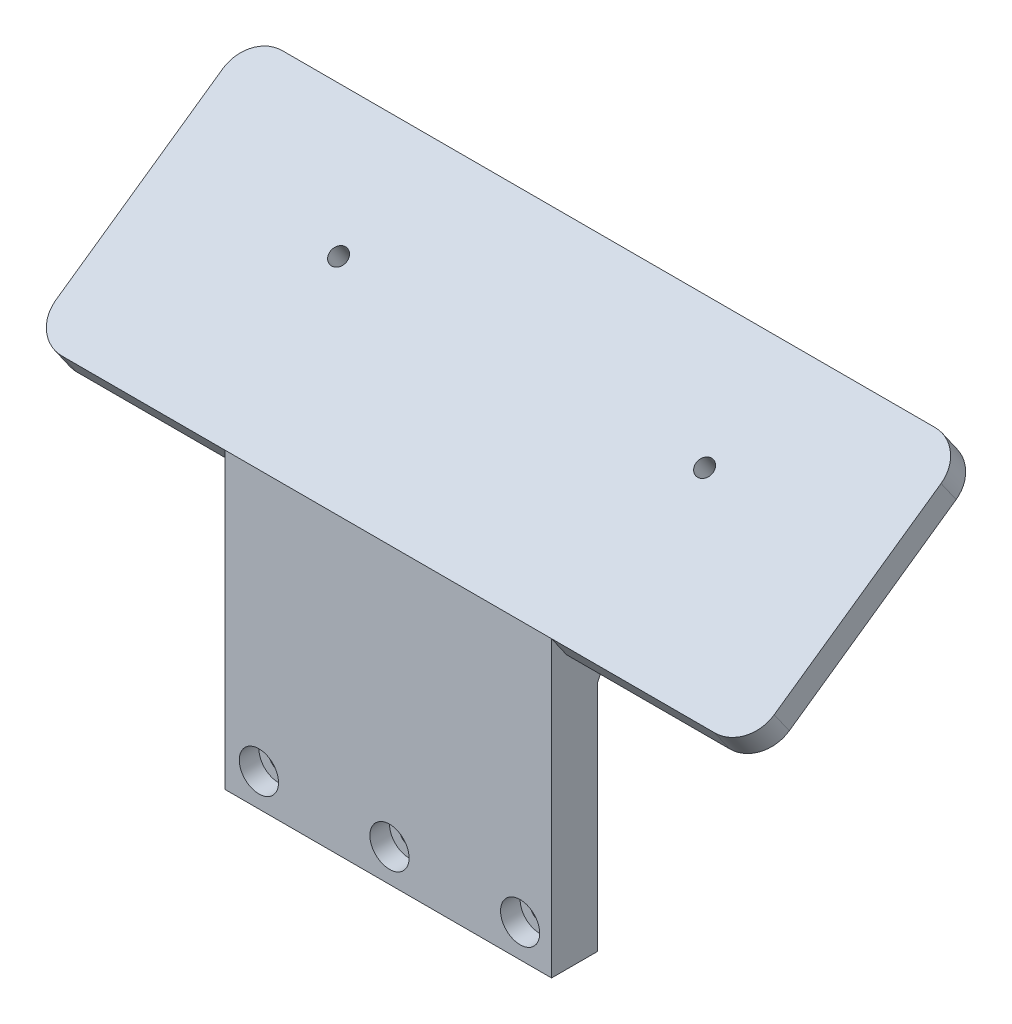
SolidWorks part; units mm, degrees
ref_plane "前视基准面" through (0, 0, 0) normal (0, 0, 1) x (1, 0, 0)
ref_plane "上视基准面" through (0, 0, 0) normal (0, 1, 0) x (1, 0, 0)
ref_plane "右视基准面" through (0, 0, 0) normal (1, 0, 0) x (0, 0, -1)
other "Configuration Table"
sketch "草图1" plane through (0, 0, 0) normal (0, 1, 0) x (1, 0, 0)
  line L0 (-68.5343, -11.9008) -> (-18.5343, -11.9008)
  line L1 (-18.5343, -11.9008) -> (-18.5343, -18.9008)
  line L2 (-18.5343, -18.9008) -> (-68.5343, -18.9008)
  line L3 (-68.5343, -18.9008) -> (-68.5343, -11.9008)
extrude "凸台-拉伸1" add sketch "草图1" along normal blind 45
sketch "草图2" plane through (0, 0, 18.9008) normal (0, 0, 1) x (1, 0, 0)
  circle A0 centre (-43.3502, 5) radius 3
  circle A1 centre (-23.3502, 5) radius 3
  circle A2 centre (-63.3502, 5) radius 3
extrude "切除-拉伸1" cut sketch "草图2" against normal blind 3
sketch "草图3" plane through (0, 0, 15.9008) normal (0, 0, 1) x (1, 0, 0)
  circle A0 centre (-23.3502, 5) radius 1.4
  circle A1 centre (-43.3502, 5) radius 1.4
  circle A2 centre (-63.3502, 5) radius 1.4
extrude "切除-拉伸2" cut sketch "草图3" against normal through all
ref_plane "基准面1" through (0, 39.0759, 27.3612) normal (0, 0.8192, 0.5736) x (1, 0, 0)
sketch "草图5" plane through (0, 39.0759, 27.3612) normal (0, 0.8192, 0.5736) x (1, 0, 0)
  line L0 (-68.5343, 10.3283) -> (-18.5343, 10.3283)
  line L3 (-68.5343, 51.52) -> (-18.5343, 51.52)
  line L4 (-18.5343, 51.52) -> (11.4657, 51.52)
  line L5 (11.4657, 51.52) -> (11.4657, 10.3283)
  line L6 (11.4657, 10.3283) -> (-18.5343, 10.3283)
  line L7 (-68.5343, 10.3283) -> (-98.5343, 10.3283)
  line L8 (-98.5343, 10.3283) -> (-98.5343, 51.52)
  line L9 (-98.5343, 51.52) -> (-68.5343, 51.52)
  line L10 (-71.3752, 35.02) -> (-15.3252, 35.02)
  circle A3 centre (-71.3752, 35.02) radius 1.3
  circle A4 centre (-15.3252, 35.02) radius 1.3
  point P19 (-43.3502, 35.02)
extrude "凸台-拉伸2" add sketch "草图5" against normal up to vertex (4.015 mm away)
sketch "草图6" plane through (-18.5343, 0, 0) normal (1, 0, 0) x (0, 0, -1)
  line L5 (-11.9008, 45) -> (-5.6109, 49.4042)
  line L6 (17.1444, 65.3377) -> (-16.5978, 41.7111) construction
  line L7 (-5.6109, 49.4042) -> (-11.9008, 35.5357)
  line L8 (-11.9008, 45) -> (-11.9008, 0) construction
  line L9 (-11.9008, 35.5357) -> (-11.9008, 45)
extrude "凸台-拉伸3" add sketch "草图6" against normal up to surface (50 mm away) up to face at (-68.5343, 26.3422, 15.6402)
fillet "圆角1" radius 5 4 edges at (-98.5343, 43.3555, 17.7493) (11.4657, 43.3555, 17.7493) (11.4657, 66.9821, -15.993) (-98.5343, 66.9821, -15.993)
sketch "草图7" plane through (0, 0, 0) normal (0, 1, 0) x (1, 0, 0)
  line L0 (-43.5343, -11.9008) -> (-43.5343, 37.1913)
  line L1 (-18.5343, -11.9008) -> (-68.5343, -11.9008) construction
  line L2 (-43.5343, 37.1913) -> (-10.2184, 37.1913)
  line L3 (-43.5343, 37.1913) -> (-76.8502, 37.1913)
  line L4 (-68.5343, -11.9008) -> (-68.5343, 19.2723)
  line L5 (-18.5343, -11.9008) -> (-18.5343, 19.2723)
  line L6 (-18.5343, -11.9008) -> (-68.5343, -11.9008)
  arc A0 (-76.8502, 37.1913) -> (-77.2379, 29.15) centre (-76.853, 33.1614) ccw
  arc A1 (-68.5343, 19.2723) -> (-77.3601, 29.1636) centre (-78.3899, 19.3615) ccw
  arc A2 (-10.2184, 37.1913) -> (-9.8307, 29.15) centre (-10.2155, 33.1614) cw
  arc A3 (-18.5343, 19.2723) -> (-9.7084, 29.1636) centre (-8.6787, 19.3615) cw
sketch "草图8" plane through (0, 10, 0) normal (0, 1, 0) x (1, 0, 0)
  circle A0 centre (-76.8502, 33.1913) radius 1.4
sketch "草图11" plane through (0, 7, 0) normal (0, 1, 0) x (1, 0, 0)
  circle A0 centre (-9.8502, 33.1913) radius 1.4
sketch "草图12" plane through (-18.5343, 0, 0) normal (1, 0, 0) x (0, 0, -1)
  line L0 (-8.964, 44.9523) -> (29.2198, 13.5)
  line L1 (-11.9008, 37.7066) -> (-7.4213, 48.7587) construction
  line L2 (29.2198, 13.5) -> (29.2198, 10)
  line L3 (29.2198, 10) -> (37.1913, 10)
  line L4 (37.1913, 10) -> (37.1913, 13.5)
  line L5 (37.1913, 13.5) -> (-6.9301, 49.9707)
  line L6 (-6.9301, 49.9707) -> (-8.964, 44.9523)
sketch "草图13" plane through (0, 10, 0) normal (0, 1, 0) x (1, 0, 0)
  line L0 (-68.3502, 37.1913) -> (-76.8502, 37.1913)
  line L1 (-76.8502, 29.1913) -> (-68.3502, 29.2198)
  line L2 (-68.3502, 37.1913) -> (-68.3502, 29.2198)
  line L5 (-9.8502, 29.1913) -> (-18.3502, 29.2198)
  line L6 (-18.3502, 37.1913) -> (-9.8502, 37.1913)
  line L7 (-18.3502, 29.2198) -> (-18.3502, 37.1913)
  arc A0 (-76.8502, 37.1913) -> (-76.8234, 29.1914) centre (-76.8502, 33.1913) ccw
  arc A2 (-9.8502, 37.1913) -> (-9.877, 29.1914) centre (-9.8502, 33.1913) cw
sketch "草图14" plane through (0, 13.5, 0) normal (0, 1, 0) x (1, 0, 0)
  circle A0 centre (-76.8502, 33.1913) radius 3
  circle A1 centre (-9.8502, 33.1913) radius 3
sketch "草图15" plane through (0, 11.5, 0) normal (0, 1, 0) x (1, 0, 0)
  circle A0 centre (-9.8502, 33.1913) radius 1.4
  circle A1 centre (-76.8502, 33.1913) radius 1.4
